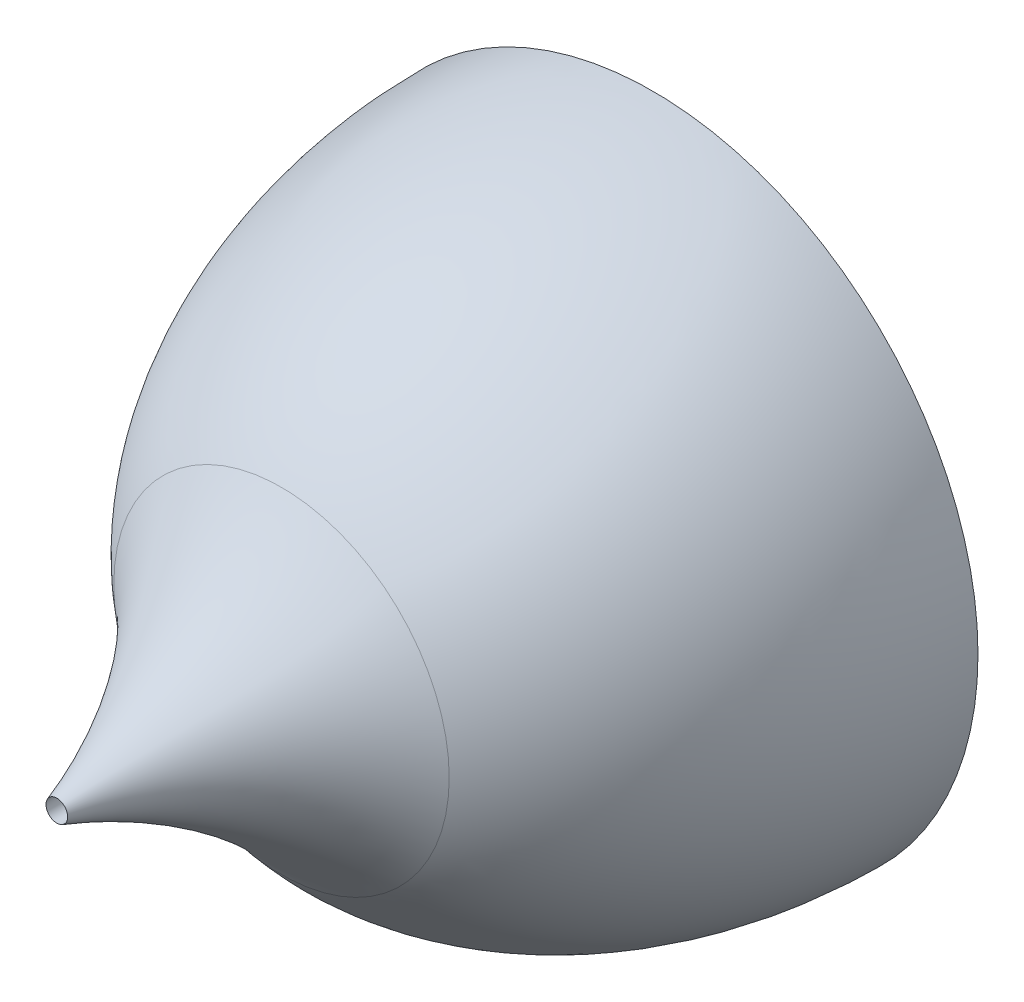
SolidWorks part; units mm, degrees
ref_plane "Plan de face" through (0, 0, 0) normal (0, 0, 1) x (1, 0, 0)
ref_plane "Plan de dessus" through (0, 0, 0) normal (0, 1, 0) x (1, 0, 0)
ref_plane "Plan de droite" through (0, 0, 0) normal (1, 0, 0) x (0, 0, -1)
sketch "Esquisse3" plane through (0, 0, 0) normal (0, 1, 0) x (1, 0, 0)
  line L0 (-29.6317, 0) -> (0, 0) construction
  line L1 (-15, 0) -> (-12, 0)
  line L3 (0, 24.4809) -> (0, -71.7147) construction
  line L5 (-0.5, -27.5) -> (-0.5, -16.9852)
  arc A0 (-0.5, -27.5) -> (-7.7378, -17.1335) centre (-21.8242, -34.6785) ccw
  ellipse E0 centre (0, 0) end of major axis (0, -20) minor radius 15 (-15, 0) -> (-7.7378, -17.1335) ccw
  ellipse E1 centre (0, 0) end of major axis (0, 17) minor radius 12 (-12, 0) -> (-0.5, -16.9852) ccw
  dimension "D5" = 0.5
  dimension "D1" = 15
  dimension "D2" = 20
  dimension "D3" = 3
  dimension "D4" = 3
revolve "Révolution1" add sketch "Esquisse3" angle 360 about L3
